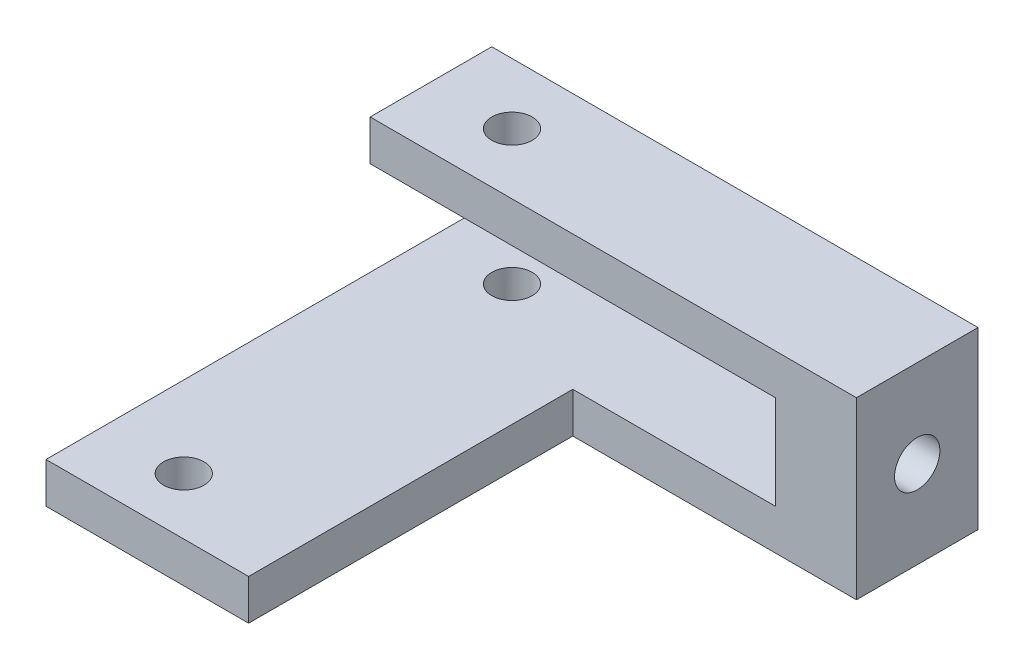
SolidWorks part; units mm, degrees
ref_plane "Front Plane" through (0, 0, 0) normal (0, 0, 1) x (1, 0, 0)
ref_plane "Top Plane" through (0, 0, 0) normal (0, 1, 0) x (1, 0, 0)
ref_plane "Right Plane" through (0, 0, 0) normal (1, 0, 0) x (0, 0, -1)
sketch "Sketch1" plane through (0, 0, 0) normal (0, 0, 1) x (1, 0, 0)
  line L0 (0, 0) -> (76.2, 0)
  line L13 (0, 0) -> (0, -27.432)
  line L14 (0, -27.432) -> (76.2, -27.432)
  line L15 (76.2, -21.082) -> (76.2, -27.432)
  line L16 (76.2, 0) -> (76.2, -6.35)
  line L17 (12.7, -6.35) -> (76.2, -6.35)
  line L18 (12.7, -21.082) -> (76.2, -21.082)
  line L19 (12.7, -6.35) -> (12.7, -21.082)
  point P2 (0, 0)
  point P5 (0, 0)
  point P7 (0, 0)
  point P9 (0, 0)
  dimension "D1" = 14.732
  dimension "D2" = 6.35
  dimension "D3" = 6.35
extrude "Boss-Extrude1" add sketch "Sketch1" along normal blind 19.05
sketch "Sketch2" plane through (0, 0, 19.05) normal (0, 0, 1) x (1, 0, 0)
  line L0 (76.2, -21.082) -> (12.7, -21.082) construction
  line L1 (44.45, -21.082) -> (76.2, -21.082)
  line L2 (44.45, -21.082) -> (44.45, -27.432)
  line L3 (44.45, -27.432) -> (76.2, -27.432)
  line L4 (76.2, -21.082) -> (76.2, -27.432)
extrude "Boss-Extrude2" add sketch "Sketch2" along normal blind 50.8
sketch "Sketch3" plane through (0, -21.082, 0) normal (0, 1, 0) x (1, 0, 0)
  circle A0 centre (63.5, -60.96) radius 3.175
  circle A1 centre (63.5, -9.525) radius 3.175
extrude "Cut-Extrude1" cut sketch "Sketch3" against normal through all both and the other way through all
sketch "Sketch4" plane through (0, 0, 0) normal (-1, 0, 0) x (0, 0, 1)
  circle A2 centre (9.525, -13.716) radius 3.556
extrude "Cut-Extrude2" cut sketch "Sketch4" against normal blind 50.8
mirror "Mirror4" about plane through (0, 0, 19.05) normal (1, 0, 0) of bodies 104
delete or keep bodies "Body-Delete/Keep 1" type delete bodies bodies 104
